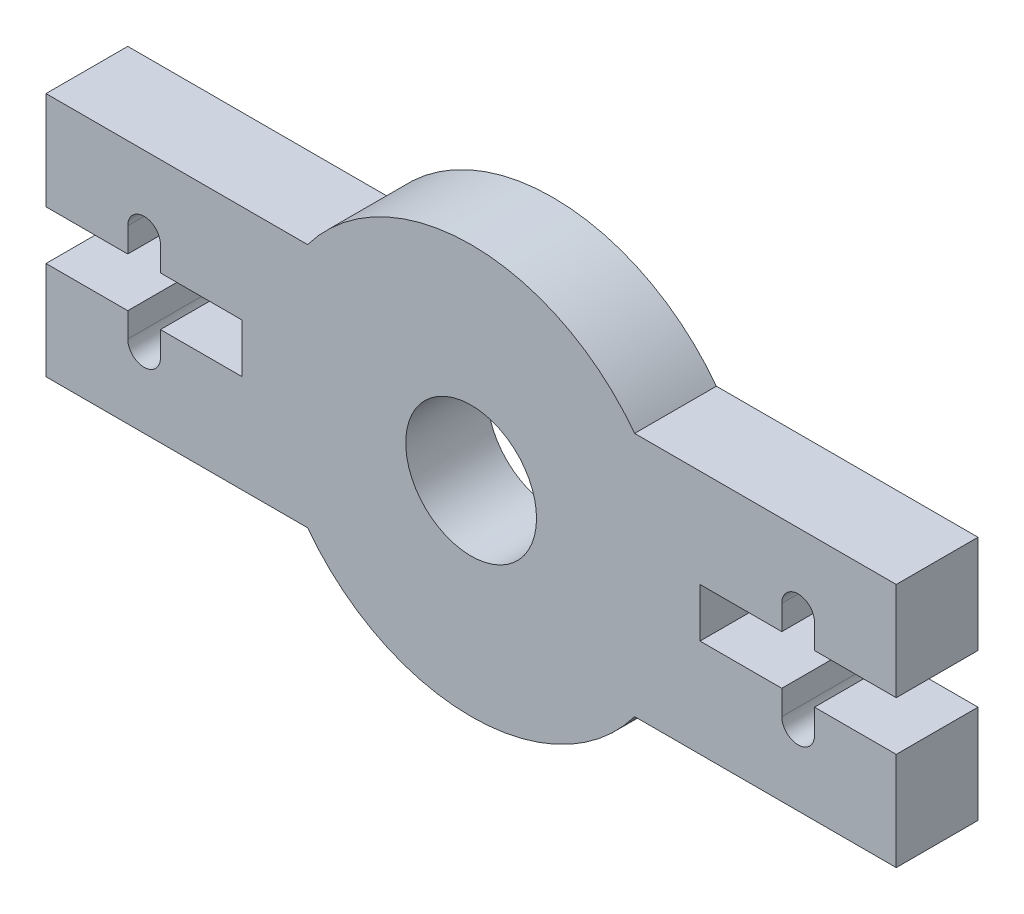
SolidWorks part; units mm, degrees
ref_plane "Front Plane" through (0, 0, 0) normal (0, 0, 1) x (1, 0, 0)
ref_plane "Top Plane" through (0, 0, 0) normal (0, 1, 0) x (1, 0, 0)
ref_plane "Right Plane" through (0, 0, 0) normal (1, 0, 0) x (0, 0, -1)
sketch "Sketch1" plane through (0, 0, 0) normal (0, 0, 1) x (1, 0, 0)
  line L0 (-20, 3) -> (-20, -3) construction
  line L1 (26, -7.5) -> (-26, -7.5)
  line L2 (26, -7.5) -> (26, 7.5)
  line L3 (26, 7.5) -> (-26, 7.5)
  line L4 (-26, -7.5) -> (-26, 7.5)
  line L5 (26, -7.5) -> (-26, 7.5) construction
  line L6 (26, 7.5) -> (-26, -7.5) construction
  line L7 (-14, -1.5) -> (-26, -1.5)
  line L8 (-14, -1.5) -> (-14, 1.5)
  line L9 (-14, 1.5) -> (-26, 1.5)
  line L10 (-26, -1.5) -> (-26, 1.5)
  line L11 (-14, -1.5) -> (-26, 1.5) construction
  line L12 (-14, 1.5) -> (-26, -1.5) construction
  line L13 (-19, 3) -> (-19, -3)
  line L14 (-21, 3) -> (-21, -3)
  line L15 (0, 7.5) -> (0, -7.5) construction
  line L16 (20, 3) -> (20, -3) construction
  line L17 (19, 3) -> (19, -3)
  line L18 (21, 3) -> (21, -3)
  line L19 (14, 1.5) -> (26, -1.5) construction
  line L20 (14, -1.5) -> (26, 1.5) construction
  line L21 (14, 1.5) -> (26, 1.5)
  line L22 (14, -1.5) -> (14, 1.5)
  line L23 (14, -1.5) -> (26, -1.5)
  circle A0 centre (0, 0) radius 12.5
  arc A1 (-19, 3) -> (-21, 3) centre (-20, 3) ccw
  arc A2 (-21, -3) -> (-19, -3) centre (-20, -3) ccw
  arc A3 (19, 3) -> (21, 3) centre (20, 3) cw
  arc A4 (21, -3) -> (19, -3) centre (20, -3) cw
  point P7 (-20, 0)
  point P14 (-20, 0)
  point P23 (20, 0)
  dimension "D1" = 25
  dimension "D2" = 52
  dimension "D3" = 3
  dimension "D4" = 12
  dimension "D5" = 2
  dimension "D6" = 8
  dimension "D7" = 15
extrude "Boss-Extrude1" add sketch "Sketch1" along normal blind 5 contours L3 A0 L1 | L3 A0 | L1 A0 | A2 L14 L7 L4 L1 A0 L3 L9 A1 L13 L8 | L18 A4 L17 L23 L22 L21 A3 L2 L3 A0 L1
sketch "Sketch2" plane through (0, 0, 5) normal (0, 0, 1) x (1, 0, 0)
  circle A0 centre (0, 0) radius 4
  dimension "D1" = 8
extrude "Cut-Extrude1" cut sketch "Sketch2" against normal blind 5
